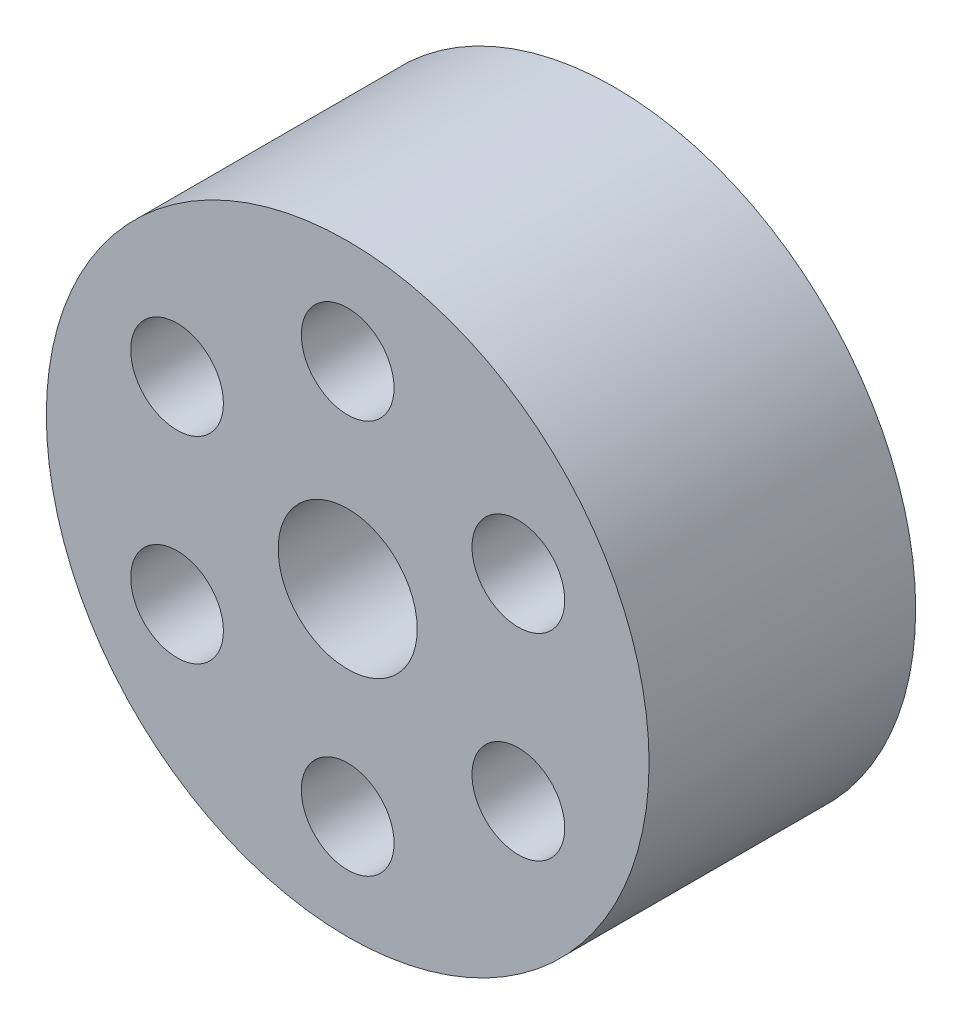
SolidWorks part; units mm, degrees
material "Plain Carbon Steel"
ref_plane "Front Plane" through (0, 0, 0) normal (0, 0, 1) x (1, 0, 0)
ref_plane "Top Plane" through (0, 0, 0) normal (0, 1, 0) x (1, 0, 0)
ref_plane "Right Plane" through (0, 0, 0) normal (1, 0, 0) x (0, 0, -1)
sketch "Esquisse1" plane through (0, 0, 0) normal (0, 0, 1) x (1, 0, 0)
  circle A0 centre (0, 0) radius 13
  dimension "D1" = 26
extrude "Boss.-Extru.1" add sketch "Esquisse1" along normal blind 11.5
sketch "Esquisse2" plane through (0, 0, 11.5) normal (0, 0, 1) x (1, 0, 0)
  line L1 (7.3612, -4.25) -> (7.3612, 4.25) construction
  line L2 (7.3612, 4.25) -> (0, 8.5) construction
  line L3 (0, 8.5) -> (-7.3612, 4.25) construction
  line L4 (-7.3612, 4.25) -> (-7.3612, -4.25) construction
  line L5 (-7.3612, -4.25) -> (0, -8.5) construction
  line L6 (0, -8.5) -> (7.3612, -4.25) construction
  circle A1 centre (0, 8.5) radius 2
  circle A2 centre (0, 0) radius 7.3612 construction
  circle A3 centre (-7.3612, 4.25) radius 2
  circle A4 centre (-7.3612, -4.25) radius 2
  circle A5 centre (0, -8.5) radius 2
  circle A6 centre (7.3612, -4.25) radius 2
  circle A7 centre (7.3612, 4.25) radius 2
  dimension "D1" = 8.5
  dimension "D2" = 4
extrude "Enlèv. mat.-Extru.1" cut sketch "Esquisse2" against normal blind 5
sketch "Esquisse3" plane through (0, 0, 11.5) normal (0, 0, 1) x (1, 0, 0)
  circle A0 centre (0, 0) radius 3
  dimension "D1" = 6
extrude "Enlèv. mat.-Extru.2" cut sketch "Esquisse3" against normal blind 4.5
